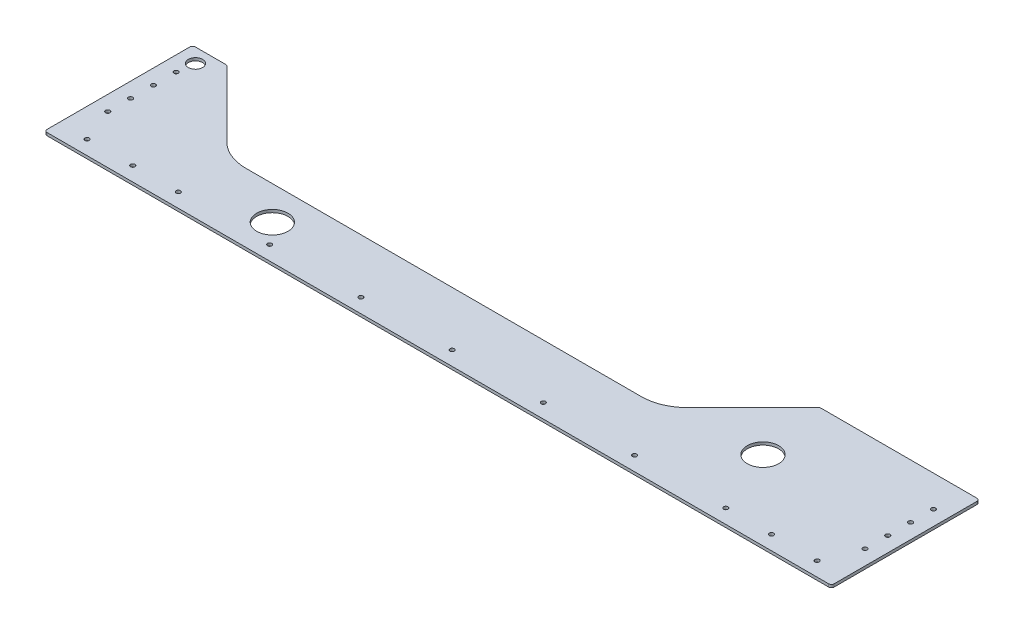
SolidWorks part; units mm, degrees
material "5052-H32"
ref_plane "Front" through (0, 0, 0) normal (0, 0, 1) x (1, 0, 0)
ref_plane "Top" through (0, 0, 0) normal (0, 1, 0) x (1, 0, 0)
ref_plane "Right" through (0, 0, 0) normal (1, 0, 0) x (0, 0, -1)
sketch "Sketch1" plane through (0, 0, 0) normal (0, 1, 0) x (1, 0, 0)
  line L0 (0, 0) -> (214.9475, 0) construction
  line L1 (214.9475, 0) -> (214.9475, 38.9255) construction
  line L2 (214.9475, 38.9255) -> (712.1677, 38.9255) construction
  line L3 (712.1677, 38.9255) -> (712.1677, 87.9475) construction
  line L4 (0, 0) -> (876.3, 0)
  line L5 (876.3, 0) -> (876.3, 165.1)
  line L6 (0, 0) -> (0, 165.1)
  line L7 (0, 165.1) -> (38.1, 165.1)
  line L8 (38.1, 165.1) -> (127, 76.2)
  line L9 (127, 76.2) -> (609.6, 76.2)
  line L10 (876.3, 165.1) -> (698.5, 165.1)
  line L11 (609.6, 76.2) -> (698.5, 165.1)
  line L12 (438.15, 0) -> (438.15, 76.2) construction
  line L13 (0, 38.1) -> (876.3, 38.1) construction
  line L14 (38.1, 165.1) -> (38.1, 38.1) construction
  line L15 (838.2, 165.1) -> (838.2, 38.1) construction
  line L16 (742.95, 15.875) -> (844.55, 15.875) construction
  line L17 (31.75, 15.875) -> (133.35, 15.875) construction
  circle A0 centre (214.9475, 38.9255) radius 17.4625
  circle A1 centre (712.1677, 87.9475) radius 17.4625
  circle A2 centre (438.15, 15.875) radius 2.4257
  circle A3 centre (539.75, 15.875) radius 2.4257
  circle A4 centre (641.35, 15.875) radius 2.4257
  circle A5 centre (742.95, 15.875) radius 2.4257
  circle A6 centre (844.55, 15.875) radius 2.4257
  circle A7 centre (31.75, 15.875) radius 2.4257
  circle A8 centre (133.35, 15.875) radius 2.4257
  circle A9 centre (234.95, 15.875) radius 2.4257
  circle A10 centre (336.55, 15.875) radius 2.4257
  circle A11 centre (16.637, 53.975) radius 2.4257
  circle A12 centre (16.637, 79.375) radius 2.4257
  circle A13 centre (16.637, 104.775) radius 2.4257
  circle A14 centre (16.637, 130.175) radius 2.4257
  circle A15 centre (859.663, 53.975) radius 2.4257
  circle A16 centre (859.663, 79.375) radius 2.4257
  circle A17 centre (859.663, 104.775) radius 2.4257
  circle A18 centre (859.663, 130.175) radius 2.4257
  circle A19 centre (82.55, 15.875) radius 2.4257
  circle A20 centre (793.75, 15.875) radius 2.4257
  circle A21 centre (19.05, 149.225) radius 7.9375
  dimension "D1" = 34.925
  dimension "D13" = 4.8514
  dimension "D23" = 15.875
  dimension "D2" = 38.9255
  dimension "D3" = 214.9475
  dimension "D4" = 497.2202
  dimension "D5" = 49.022
  dimension "D6" = 876.3
  dimension "D7" = 38.1
  dimension "D8" = 165.1
  dimension "D9" = 45
  dimension "D10" = 76.2
  dimension "D11" = 45
  dimension "D12" = 177.8
  dimension "D14" = 15.875
  dimension "D16" = 101.6
  dimension "D17" = 38.1
  dimension "D18" = 38.1
  dimension "D19" = 16.637
  dimension "D20" = 15.875
  dimension "D22" = 25.4
  dimension "D24" = 19.05
  dimension "D25" = 19.05
  dimension "D15" = 5
  dimension "D21" = 4
extrude "Boss-Extrude1" add sketch "Sketch1" along normal blind 3.175 contours L11 L9 L8 L7 L6 L4 L5 L10 A17 A15 A14 A13 A12 A11 A9 A7 A6 A5 A4 A3 A2 A1 A0 A8 A10 A16 A18
fillet "Fillet1" radius 50.8 2 edges at (609.6, 1.5875, -76.2) (127, 1.5875, -76.2)
fillet "Fillet2" radius 3.175 6 edges at (698.5, 1.5875, -165.1) (876.3, 1.5875, -165.1) (876.3, 1.5875, 0) (0, 1.5875, -165.1) (38.1, 1.5875, -165.1) (0, 1.5875, 0)
